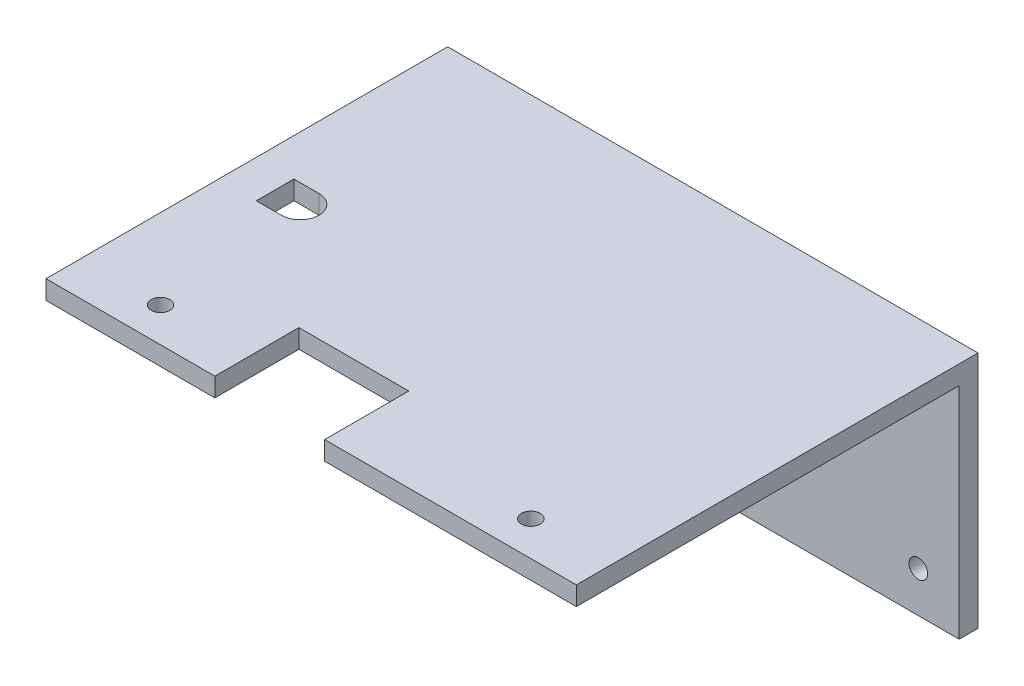
SolidWorks part; units mm, degrees
ref_plane "前视基准面" through (0, 0, 0) normal (0, 0, 1) x (1, 0, 0)
ref_plane "上视基准面" through (0, 0, 0) normal (0, 1, 0) x (1, 0, 0)
ref_plane "右视基准面" through (0, 0, 0) normal (1, 0, 0) x (0, 0, -1)
other "Configuration Table"
sketch "草图1" plane through (0, 0, 0) normal (0, 0, 1) x (1, 0, 0)
  line L0 (0, 0) -> (42.25, 0)
  line L1 (0, 0) -> (-42.25, 0)
  line L6 (0, 35) -> (-42.25, 35)
  line L8 (0, 35) -> (42.25, 35)
  line L9 (42.25, 35) -> (42.25, 0)
  line L10 (-42.25, 35) -> (-42.25, 0)
  circle A0 centre (-29.5, 17) radius 1.52
  circle A1 centre (29.5, 17) radius 1.52
extrude "凸台-拉伸2" add sketch "草图1" along normal blind 3 contours A0 | L0 L9 L8 L6 L10 L1 | A1
sketch "草图2" plane through (0, 0, 0) normal (0, 0, -1) x (-1, 0, 0)
  line L0 (42.25, 35) -> (42.25, 0) construction
  line L1 (-42.25, 0) -> (42.25, 0)
  line L2 (-42.25, 0) -> (-42.25, 3)
  line L3 (-42.25, 3) -> (42.25, 3)
  line L4 (42.25, 0) -> (42.25, 3)
extrude "凸台-拉伸3" add sketch "草图2" along normal blind 58 contours L2 L1 L4 L3
sketch "草图3" plane through (0, 0, 0) normal (0, 0, -1) x (-1, 0, 0)
  line L0 (-42.25, 3) -> (42.25, 3) construction
  line L1 (-42.25, 35) -> (-39.25, 35)
  line L2 (-42.25, 35) -> (-42.25, 3)
  line L3 (-42.25, 3) -> (-39.25, 3)
  line L4 (-39.25, 35) -> (-39.25, 3)
  line L6 (42.25, 35) -> (39.25, 35)
  line L7 (42.25, 35) -> (42.25, 3)
  line L8 (42.25, 3) -> (39.25, 3)
  line L9 (39.25, 35) -> (39.25, 3)
  line M10 (-42.25, 3) -> (42.25, 3)
  line M11 (42.25, 3) -> (42.25, 35)
  line M12 (42.25, 35) -> (-42.25, 35)
extrude "凸台-拉伸4" add sketch "草图3" along normal blind 58 contours L9 M12 M10 M11 | L2 L1 L4 L3
sketch "草图5" plane through (42.25, 0, 0) normal (1, 0, 0) x (0, 0, -1)
  line L0 (-3, 0) -> (-3, 17)
  line L1 (-3, 35) -> (-3, 0) construction
  line L2 (-3, 17) -> (16, 17)
  circle A0 centre (16, 17) radius 2.1
extrude "切除-拉伸1" cut sketch "草图5" against normal blind 58
sketch "草图12" plane through (0, 0, 0) normal (0, 0, -1) x (-1, 0, 0)
  line L0 (-35, 35) -> (-24, 35)
  line L1 (-29.5, 28) -> (-24, 28)
  line L2 (24, 35) -> (35, 35)
  line L3 (-24, 28) -> (-24, 35)
  line L4 (-29.5, 28) -> (-35, 28)
  line L5 (-35, 28) -> (-35, 35)
  line L7 (29.5, 28) -> (35, 28)
  line L8 (29.5, 28) -> (24, 28)
  line L9 (24, 35) -> (24, 28)
  line L10 (35, 35) -> (35, 28)
extrude "凸台-拉伸9" add sketch "草图12" along normal blind 5 contours L5 L4 L1 L3 L0 | L8 L9 L2 L10 L7
sketch "草图14" plane through (0, 35, 0) normal (0, 1, 0) x (1, 0, 0)
  line L0 (-35, 5) -> (-24, 0)
  line L1 (24, 5) -> (35, 0)
  circle A0 centre (-29.5, 2.5) radius 1.49
  circle A1 centre (29.5, 2.5) radius 1.49
extrude "切除-拉伸4" cut sketch "草图14" against normal blind 4 contours L0 A0 | L0 A0 | L1 A1 | L1 A1
sketch "草图15" plane through (0, 3, 0) normal (0, 1, 0) x (1, 0, 0)
  line L1 (-39.25, 58) -> (-32.25, 58)
  line L2 (-39.25, 58) -> (-39.25, 51)
  line L3 (-39.25, 51) -> (-32.25, 51)
  line L4 (-32.25, 58) -> (-32.25, 51)
  line L5 (39.25, 58) -> (32.25, 58)
  line L6 (39.25, 58) -> (39.25, 51)
  line L7 (39.25, 51) -> (32.25, 51)
  line L8 (32.25, 58) -> (32.25, 51)
  line M9 (39.25, 0) -> (39.25, 58)
  line M10 (39.25, 58) -> (-39.25, 58)
extrude "凸台-拉伸10" add sketch "草图15" along normal blind 7 contours L8 L7 M10 M9 | L2 L1 L4 L3
sketch "草图16" plane through (0, 0, -58) normal (0, 0, -1) x (-1, 0, 0)
  line L0 (-39.25, 10) -> (-32.25, 3)
  line L1 (32.25, 3) -> (39.25, 10)
  circle A0 centre (-35.75, 6.5) radius 1.49
  circle A1 centre (35.75, 6.5) radius 1.49
extrude "切除-拉伸5" cut sketch "草图16" against normal blind 5 contours L0 A0 | L0 A0 | L1 A1 | L1 A1
sketch "草图17" plane through (42.25, 0, 0) normal (1, 0, 0) x (0, 0, -1)
  line L0 (58, 35) -> (58, 0)
  line L1 (-3, 35) -> (58, 35)
  line L2 (-3, 35) -> (-3, 38)
  line L3 (-3, 38) -> (58, 38)
  line L5 (58, 0) -> (61, 0)
  line L7 (58, 38) -> (61, 38)
  line L8 (61, 0) -> (61, 38)
extrude "凸台-拉伸11" add sketch "草图17" against normal blind 84.5 contours L0 L5 L8 L7 L3 L2 L1
sketch "草图19" plane through (0, 0, 0) normal (0, 0, -1) x (-1, 0, 0)
  circle A0 centre (-35.75, 6.5) radius 1.49
  circle A1 centre (35.75, 6.5) radius 1.49
extrude "切除-拉伸6" cut sketch "草图19" along normal blind 84.5 contours A0 | A1
sketch "草图20" plane through (0, 28, 0) normal (0, -1, 0) x (1, 0, 0)
  circle A0 centre (-29.5, -2.5) radius 1.49
  circle A1 centre (29.5, -2.5) radius 1.49
extrude "切除-拉伸7" cut sketch "草图20" against normal blind 84.5
sketch "草图21" plane through (-42.25, 0, 0) normal (-1, 0, 0) x (0, 0, 1)
  line L1 (3, 0) -> (-58, 0)
  line L2 (3, 0) -> (3, 35)
  line L3 (3, 35) -> (-58, 35)
  line L4 (-58, 0) -> (-58, 35)
extrude "切除-拉伸8" cut sketch "草图21" against normal blind 84.5
sketch "草图22" plane through (0, 35, 0) normal (0, -1, 0) x (1, 0, 0)
  line L0 (-42.25, -48) -> (-17.25, -48)
  line L1 (-42.25, 3) -> (-42.25, -58) construction
  line L2 (-17.25, -48) -> (-17.25, -58)
  line L3 (-42.25, -58) -> (42.25, -58) construction
  line L4 (42.25, -48) -> (17.25, -48)
  line L5 (42.25, 3) -> (42.25, -58) construction
  line L6 (-17.25, -48) -> (17.25, -48)
  line L7 (17.25, -48) -> (17.25, -58)
  line L8 (17.25, -58) -> (-17.25, -58)
  line M4 (-42.25, -58) -> (42.25, -58)
extrude "切除-拉伸9" cut sketch "草图22" against normal blind 1.5 contours L7 L6 L2 M4
sketch "草图23" plane through (0, 38, 0) normal (0, 1, 0) x (1, 0, 0)
  line L4 (-32.25, 24.5) -> (-35.25, 24.5)
  line L5 (-35.25, 24.5) -> (-35.25, 27.5)
  line L6 (-35.25, 27.5) -> (-35.25, 30.5)
  line L7 (-35.25, 30.5) -> (-32.25, 30.5)
  arc A1 (-32.25, 24.5) -> (-32.25, 30.5) centre (-32.25, 27.5) ccw
extrude "切除-拉伸10" cut sketch "草图23" against normal blind 3
sketch "草图24" plane through (0, 38, 0) normal (0, 1, 0) x (1, 0, 0)
  line L0 (2.15, 10.4) -> (2.15, -3)
  line L1 (-42.25, -3) -> (42.25, -3) construction
  line L5 (-1.6992, -3) -> (2.15, -3)
  line L6 (29.5, 2.5) -> (29.5, -3)
  line L8 (-12.1992, -3) -> (-1.6992, -3)
  line L11 (-42.25, -3) -> (-15.35, -3)
  line L12 (-15.35, -3) -> (-15.35, 10.4)
  line L13 (-15.35, 10.4) -> (2.15, 10.4)
  line L14 (-15.35, -3) -> (-12.6992, -3)
extrude "切除-拉伸11" cut sketch "草图24" against normal blind 3
sketch "草图26" plane through (0, 0, -61) normal (0, 0, -1) x (-1, 0, 0)
  text T0 "晨江苇" font "宋体" height in points 42
sketch "草图27" plane through (0, 38, 0) normal (0, 1, 0) x (1, 0, 0)
  line L1 (-35.25, 30.5) -> (-36.25, 30.5)
  line L2 (-35.25, 30.5) -> (-35.25, 24.5)
  line L3 (-35.25, 24.5) -> (-36.25, 24.5)
  line L4 (-36.25, 30.5) -> (-36.25, 24.5)
extrude "切除-拉伸12" cut sketch "草图27" against normal blind 10
extrude "切除-拉伸13" cut sketch "草图26" against normal blind 1
